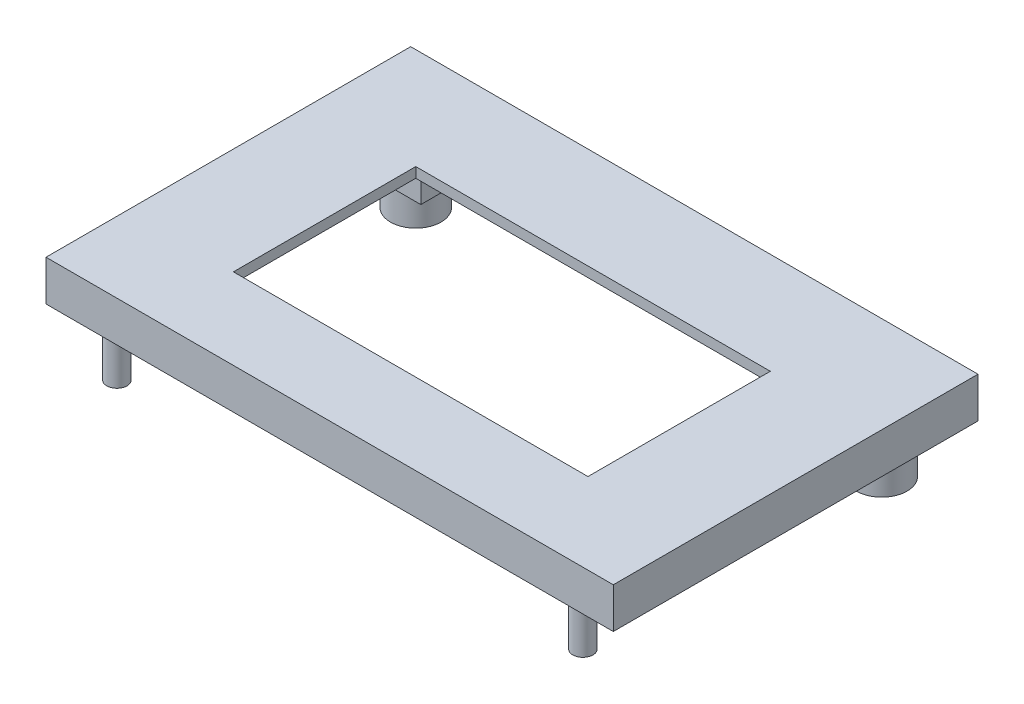
SolidWorks part; units mm, degrees
ref_plane "前视基准面" through (0, 0, 0) normal (0, 0, 1) x (1, 0, 0)
ref_plane "上视基准面" through (0, 0, 0) normal (0, 1, 0) x (1, 0, 0)
ref_plane "右视基准面" through (0, 0, 0) normal (1, 0, 0) x (0, 0, -1)
sketch "草图1" plane through (0, 0, 0) normal (0, 1, 0) x (1, 0, 0)
  line L1 (0, 0) -> (56, 0)
  line L2 (0, 0) -> (0, -36)
  line L3 (0, -36) -> (56, -36)
  line L4 (56, 0) -> (56, -36)
  line L5 (1, -32) -> (55, -32)
  line L6 (1, -32) -> (1, -9)
  line L7 (1, -9) -> (55, -9)
  line L8 (55, -32) -> (55, -9)
  line L9 (10, -9) -> (46, -9)
  line L10 (10, -9) -> (10, -1)
  line L11 (10, -1) -> (46, -1)
  line L12 (46, -9) -> (46, -1)
  line L13 (10, -32) -> (46, -32)
  line L14 (10, -32) -> (10, -35)
  line L15 (10, -35) -> (46, -35)
  line L16 (46, -32) -> (46, -35)
  dimension "D1" = 56
  dimension "D2" = 36
  dimension "D3" = 1
  dimension "D4" = 1
  dimension "D5" = 9
  dimension "D6" = 1
  dimension "D7" = 10
  dimension "D8" = 10
  dimension "D9" = 4
  dimension "D10" = 1
extrude "凸台-拉伸3" add sketch "草图1" along normal blind 3 contours L4 L1 L2 L3 L5 L16 L15 L14 L6 L7 L10 L11 L12 L8
ref_plane "基准面1" through (0, 3, 0) normal (0, 1, 0) x (1, 0, 0)
sketch "草图2" plane through (0, 3, 0) normal (0, 1, 0) x (1, 0, 0)
  line L0 (10, -34.4069) -> (10, -32) construction
  line L1 (0, 0) -> (56, 0)
  line L2 (0, 0) -> (0, -36)
  line L3 (0, -36) -> (56, -36)
  line L4 (56, 0) -> (56, -36)
  line L5 (10.5, -10) -> (45.5, -10)
  line L6 (10.5, -10) -> (10.5, -28)
  line L7 (10.5, -28) -> (45.5, -28)
  line L8 (45.5, -10) -> (45.5, -28)
  line L11 (46, -34.278) -> (46, -32.394) construction
  dimension "D1" = 10
  dimension "D2" = 8
  dimension "D3" = 0.5
  dimension "D4" = 0.5
extrude "凸台-拉伸4" add sketch "草图2" along normal blind 1
ref_plane "基准面2" through (0, 0, 0) normal (0, -1, 0) x (-1, 0, 0)
sketch "草图3" plane through (0, 0, 0) normal (0, -1, 0) x (-1, 0, 0)
  line L0 (-56, 0) -> (-56, -36) construction
  line L1 (0, -36) -> (-56, -36) construction
  line L2 (0, 0) -> (0, -36) construction
  line L3 (0, 0) -> (-56, 0) construction
  circle A0 centre (-51, -34) radius 1
  circle A1 centre (-5, -34) radius 1
  circle A2 centre (-51, -4.5) radius 2.5
  circle A3 centre (-5, -4.5) radius 2.5
  dimension "D1" = 5
  dimension "D3" = 5
  dimension "D5" = 5
  dimension "D7" = 5
  dimension "D2" = 2
  dimension "D4" = 2
  dimension "D6" = 4.5
  dimension "D8" = 4.5
extrude "凸台-拉伸5" add sketch "草图3" along normal blind 5
